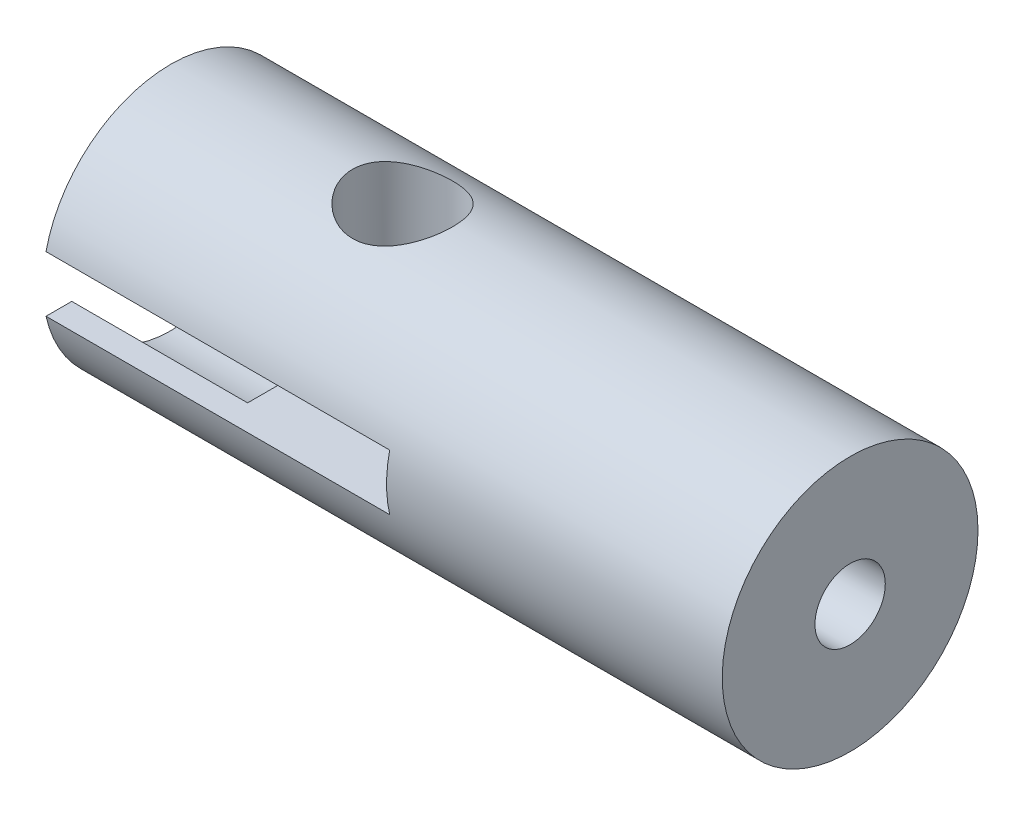
SolidWorks part; units mm, degrees
material "AISI 1020"
ref_plane "Front Plane" through (0, 0, 0) normal (0, 0, 1) x (1, 0, 0)
ref_plane "Top Plane" through (0, 0, 0) normal (0, 1, 0) x (1, 0, 0)
ref_plane "Right Plane" through (0, 0, 0) normal (1, 0, 0) x (0, 0, -1)
sketch "Sketch1" plane through (0, 0, 0) normal (0, 1, 0) x (1, 0, 0)
  line L0 (-77.5, 0) -> (77.5, 0) construction
  line L2 (-77.5, 0) -> (-77.5, -16)
  line L3 (-77.5, -16) -> (77.5, -16)
  line L4 (77.5, 0) -> (77.5, -16)
  line L5 (0, 0) -> (77.5, -16) construction
  line L6 (-77.5, -16) -> (0, 0) construction
  line L7 (-77.5, 0) -> (77.5, 0)
  point P0 (0, 0)
  point P2 (0, 0)
  dimension "D1" = 155
  dimension "D2" = 16
revolve "Revolve1" add sketch "Sketch1" angle 360 about L7
sketch "Sketch2" plane through (0, 0, 0) normal (0, 1, 0) x (1, 0, 0)
  line L1 (-77.5, 16) -> (-77.5, -16) construction
  circle A0 centre (-53.5, 0) radius 6.25
  dimension "D1" = 12.5
  dimension "D2" = 24
extrude "Cut-Extrude1" cut sketch "Sketch2" against normal through all both and the other way through all
sketch "Sketch4" plane through (-77.5, 0, 0) normal (-1, 0, 0) x (0, 0, 1)
  line L1 (-25, 3.5) -> (25, 3.5)
  line L2 (-25, 3.5) -> (-25, -3.5)
  line L3 (-25, -3.5) -> (25, -3.5)
  line L4 (25, 3.5) -> (25, -3.5)
  line L5 (-25, 3.5) -> (25, -3.5) construction
  line L6 (-25, -3.5) -> (25, 3.5) construction
  point P0 (0, 0)
  dimension "D1" = 7
  dimension "D2" = 50
extrude "Cut-Extrude3" cut sketch "Sketch4" against normal blind 38
sketch "Sketch6" plane through (-77.5, 0, 0) normal (-1, 0, 0) x (0, 0, 1)
  line L1 (-15.6125, 3.5) -> (15.6125, 3.5)
  line L3 (-15.6125, 3.5) -> (15.6125, 3.5)
  line L4 (15.6125, -3.5) -> (-15.6125, -3.5)
  arc A1 (15.6125, 3.5) -> (-15.6125, 3.5) centre (0, 0) ccw
  arc A2 (15.6125, 3.5) -> (-15.6125, 3.5) centre (0, 0) ccw
  arc A4 (-15.6125, -3.5) -> (15.6125, -3.5) centre (0, 0) ccw
  dimension "D1" = 0
extrude "Boss-Extrude1" add sketch "Sketch6" along normal blind 5
sketch "Sketch7" plane through (-82.5, 0, 0) normal (-1, 0, 0) x (0, 0, 1)
  point P0 (0, 0)
hole_wizard "Ø24.0 (24) Diameter Hole1" positions "Sketch10" profile "Sketch11" hole size "Ø24.0" standard "ANSI Metric"
sketch "Sketch10" plane through (-82.5, 0, 0) normal (-1, 0, 0) x (0, 0, 1)
  point P0 (0, 0)
sketch "Sketch11" plane through (-82.5, 0, 0) normal (0, 1, 0) x (0, 0, 1)
  line L0 (0, 0) -> (0, 27.2103)
  line L1 (0, 27.2103) -> (12, 20)
  line L2 (12, 20) -> (12, 0)
  line L5 (12, 0) -> (0, 0)
  line L10 (0, 27.2103) -> (-12, 20) construction
  line L11 (0, -6.35) -> (0, 107.95) construction
  dimension "Hole Dia." = 24
  dimension "Hole Depth" = 20
  dimension "Drill Angle" = 118
sketch "Sketch24" plane through (-82.5, 0, 0) normal (-1, 0, 0) x (0, 0, 1)
  circle A0 centre (0, 0) radius 12.875
  dimension "D1" = 25.75
extrude "Cut-Extrude12" cut sketch "Sketch24" against normal blind 22
sketch "Sketch12" plane through (77.5, 0, 0) normal (1, 0, 0) x (0, 0, -1)
  circle A0 centre (0, 0) radius 16 construction
  circle A1 centre (0, 0) radius 16
  circle A2 centre (0, 0) radius 10
  dimension "D1" = 20
extrude "Cut-Extrude6" cut sketch "Sketch12" against normal blind 35
sketch "Sketch13" plane through (77.5, 0, 0) normal (1, 0, 0) x (0, 0, -1)
  circle A0 centre (0, 0) radius 6
  dimension "D1" = 12
extrude "Boss-Extrude2" add sketch "Sketch13" along normal blind 15
sketch "Sketch14" plane through (77.5, 0, 0) normal (1, 0, 0) x (0, 0, -1)
  line L1 (-0.5, 10.5) -> (0.5, 10.5)
  line L2 (-0.5, 10.5) -> (-0.5, 9.5)
  line L3 (-0.5, 9.5) -> (0.5, 9.5)
  line L4 (0.5, 10.5) -> (0.5, 9.5)
  line L5 (-0.5, 10.5) -> (0.5, 9.5) construction
  line L6 (-0.5, 9.5) -> (0.5, 10.5) construction
  circle A0 centre (0, 0) radius 10 construction
  point P0 (0, 10)
  dimension "D1" = 1
  dimension "D2" = 1
chamfer "Chamfer2" distance 0.5 angle 45 1 edges at (92.5, 0, -6)
ref_plane "Plane1" through (47.5, 0, 0) normal (1, 0, 0) x (0, 0, -1)
sketch "Sketch17" plane through (47.5, 0, 0) normal (1, 0, 0) x (0, 0, -1)
  circle A0 centre (0, 0) radius 12.5
  circle A1 centre (0, 0) radius 16 construction
  circle A2 centre (0, 0) radius 16
  dimension "D1" = 25
extrude "Cut-Extrude9" cut sketch "Sketch17" against normal blind 75
sketch "Sketch19" plane through (0, 0, 0) normal (0, 1, 0) x (1, 0, 0)
  line L0 (-27.5, 16) -> (42.5, 12.5)
  line L1 (42.5, 12.5) -> (42.5, 0)
  line L2 (42.5, -10) -> (42.5, 10) construction
  line L3 (42.5, 0) -> (-27.5, 0)
  line L4 (-27.5, -16) -> (-27.5, 16) construction
  line L5 (-27.5, 0) -> (-27.5, 16)
extrude "Boss-Extrude3" add sketch "Sketch14" against normal blind 35
pattern_circular "CirPattern1" count 32 over 360 about axis through (0, 0, 0) along (1, 0, 0) of "Boss-Extrude3"
sketch "Sketch20" plane through (0, 0, 0) normal (0, 1, 0) x (1, 0, 0)
  line L0 (-27.5, -16) -> (-27.5, 16) construction
  line L1 (-27.5, 16) -> (102.1779, 16)
  line L2 (-27.5, 16) -> (-27.5, -16)
  line L3 (-27.5, -16) -> (102.1779, -16)
  line L4 (102.1779, 16) -> (102.1779, -16)
extrude "Cut-Extrude10" cut sketch "Sketch20" against normal through all both and the other way through all
sketch "Sketch22" plane through (-27.5, 0, 0) normal (1, 0, 0) x (0, 0, -1)
  circle A1 centre (0, 0) radius 16
  circle A2 centre (0, 0) radius 16
  dimension "D1" = 0
extrude "Boss-Extrude4" add sketch "Sketch22" along normal blind 30
sketch "Sketch25" plane through (2.5, 0, 0) normal (1, 0, 0) x (0, 0, -1)
  point P0 (0, 0)
hole_wizard "M10x1.25 Tapped Hole1" positions "Sketch26" profile "Sketch27" tap size "M10x1.25" standard "ANSI Metric"
sketch "Sketch26" plane through (2.5, 0, 0) normal (1, 0, 0) x (0, 0, -1)
  point P0 (0, 0)
sketch "Sketch27" plane through (2.5, 0, 0) normal (0, 1, 0) x (0, 0, -1)
  line L0 (0, 0) -> (0, 32.6438)
  line L1 (0, 32.6438) -> (4.4, 30)
  line L2 (4.4, 30) -> (4.4, 0)
  line L5 (4.4, 0) -> (0, 0)
  line L10 (0, 32.6438) -> (-4.4, 30) construction
  line L11 (0, -6.35) -> (0, 107.95) construction
  dimension "Tap Drill Dia." = 8.8
  dimension "Tap Drill Depth" = 30
  dimension "Drill Angle" = 118
cosmetic thread "Hole Thread1" parameters "D1"=20, "D2"=10
